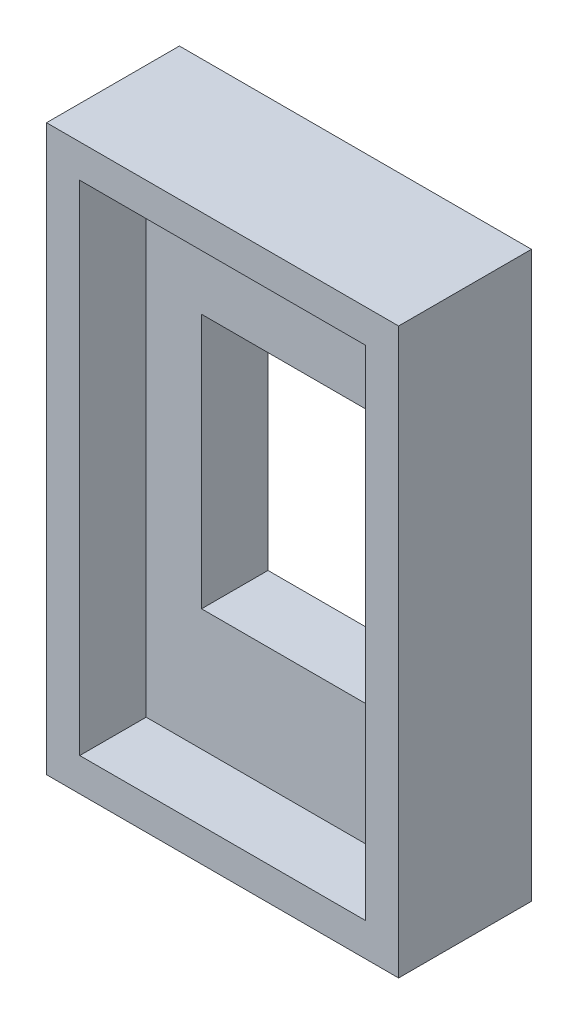
SolidWorks part; units mm, degrees
ref_plane "Front Plane" through (0, 0, 0) normal (0, 0, 1) x (1, 0, 0)
ref_plane "Top Plane" through (0, 0, 0) normal (0, 1, 0) x (1, 0, 0)
ref_plane "Right Plane" through (0, 0, 0) normal (1, 0, 0) x (0, 0, -1)
sketch "Sketch3" plane through (0, 0, 0) normal (0, 0, 1) x (1, 0, 0)
  line L1 (26.5, -42.5) -> (-26.5, -42.5)
  line L2 (26.5, -42.5) -> (26.5, 42.5)
  line L3 (26.5, 42.5) -> (-26.5, 42.5)
  line L4 (-26.5, -42.5) -> (-26.5, 42.5)
  line L5 (26.5, -42.5) -> (-26.5, 42.5) construction
  line L6 (26.5, 42.5) -> (-26.5, -42.5) construction
  point P0 (0, 0)
  dimension "D1" = 53
  dimension "D2" = 85
extrude "Boss-Extrude1" add sketch "Sketch3" along normal blind 20
sketch "Sketch4" plane through (0, 0, 20) normal (0, 0, 1) x (1, 0, 0)
  line L0 (26.5, 42.5) -> (-26.5, 42.5) construction
  line L1 (21.5, -37.5) -> (-21.5, -37.5)
  line L2 (21.5, -37.5) -> (21.5, 37.5)
  line L3 (21.5, 37.5) -> (-21.5, 37.5)
  line L4 (-21.5, -37.5) -> (-21.5, 37.5)
  line L5 (21.5, -37.5) -> (-21.5, 37.5) construction
  line L6 (21.5, 37.5) -> (-21.5, -37.5) construction
  line L7 (-26.5, 42.5) -> (-26.5, -42.5) construction
  point P0 (0, 0)
  dimension "D1" = 5
  dimension "D2" = 5
extrude "Cut-Extrude1" cut sketch "Sketch4" against normal blind 10
sketch "Sketch5" plane through (0, 0, 0) normal (0, 0, -1) x (-1, 0, 0)
  line L1 (13.1607, -19.1998) -> (-13.1607, -19.1998)
  line L2 (13.1607, -19.1998) -> (13.1607, 19.1998)
  line L3 (13.1607, 19.1998) -> (-13.1607, 19.1998)
  line L4 (-13.1607, -19.1998) -> (-13.1607, 19.1998)
  line L5 (13.1607, -19.1998) -> (-13.1607, 19.1998) construction
  line L6 (13.1607, 19.1998) -> (-13.1607, -19.1998) construction
  point P0 (0, 0)
extrude "Cut-Extrude2" cut sketch "Sketch5" against normal blind 10
